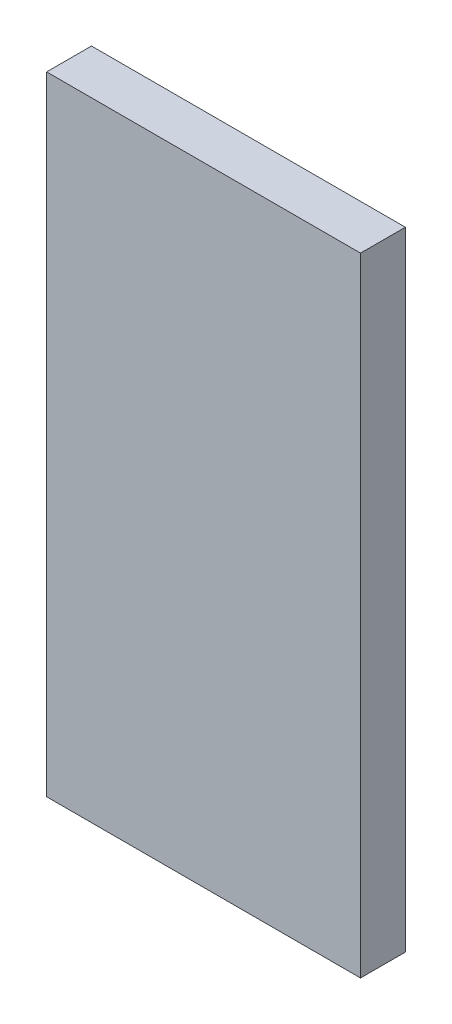
SolidWorks part; units mm, degrees
ref_plane "前视基准面" through (0, 0, 0) normal (0, 0, 1) x (1, 0, 0)
ref_plane "上视基准面" through (0, 0, 0) normal (0, 1, 0) x (1, 0, 0)
ref_plane "右视基准面" through (0, 0, 0) normal (1, 0, 0) x (0, 0, -1)
sketch "草图1" plane through (0, 0, 0) normal (0, 0, 1) x (1, 0, 0)
  line L0 (21, 21) -> (-21, 21)
  line L5 (-21, 21) -> (21, 21)
  line L6 (-21, 21) -> (-21, -21)
  line L7 (-21, -21) -> (21, -21)
  line L8 (21, 21) -> (21, -21)
  line L9 (-21, 21) -> (21, -21) construction
  line L10 (-21, -21) -> (21, 21) construction
  line L11 (21, 21) -> (21, 63)
  line L12 (-21, 21) -> (-21, 63)
  line L13 (21, 63) -> (-21, 63)
  point P0 (0, 0)
  dimension "D1" = 42
  dimension "D2" = 42
extrude "凸台-拉伸1" add sketch "草图1" along normal blind 6 contours L11 L13 L12 L0 | L8 L0 L6 L7
